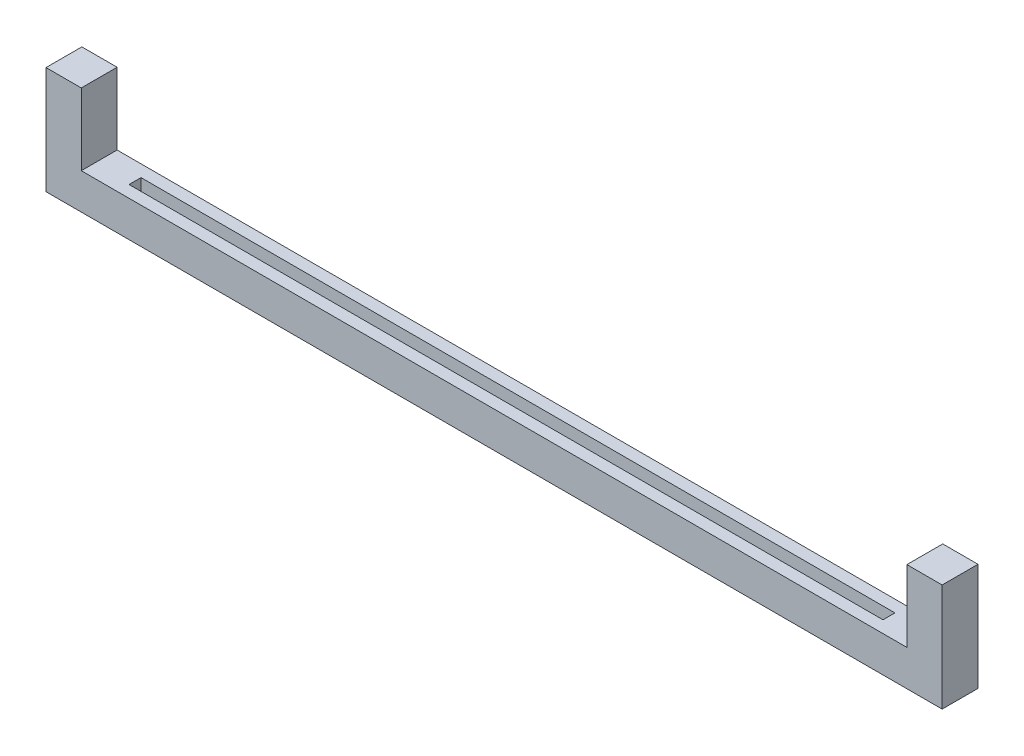
SolidWorks part; units mm, degrees
ref_plane "Front Plane" through (0, 0, 0) normal (0, 0, 1) x (1, 0, 0)
ref_plane "Top Plane" through (0, 0, 0) normal (0, 1, 0) x (1, 0, 0)
ref_plane "Right Plane" through (0, 0, 0) normal (1, 0, 0) x (0, 0, -1)
sketch "Sketch1" plane through (0, 0, 0) normal (0, 0, 1) x (1, 0, 0)
  line L0 (-62.5, 7.5) -> (62.5, -7.5) construction
  line L1 (-62.5, 7.5) -> (62.5, 7.5)
  line L2 (-62.5, 7.5) -> (-62.5, -7.5)
  line L3 (-62.5, -7.5) -> (62.5, -7.5)
  line L4 (62.5, 7.5) -> (62.5, -7.5)
  line L5 (62.5, 7.5) -> (-62.5, -7.5) construction
  line L7 (-57.58, 2.5) -> (57.58, 2.5)
  line L8 (-57.58, 2.5) -> (-57.58, -2.5)
  line L9 (-57.58, -2.5) -> (57.58, -2.5)
  line L10 (57.58, 2.5) -> (57.58, -2.5)
  point P4 (0, 0)
  dimension "D1" = 125
  dimension "D2" = 15
  dimension "D3" = 4.92
  dimension "D4" = 5
  dimension "D5" = 5
  dimension "D6" = 4.92
extrude "Slider Main Body" add sketch "Sketch1" along normal blind 5
sketch "Sketch5" plane through (0, -7.5, 0) normal (0, -1, 0) x (1, 0, 0)
  line L0 (57.58, 5) -> (57.58, 0) construction
  line L2 (57.58, 5) -> (57.58, 0)
  line L4 (62.5, 5) -> (-62.5, 5)
  line L5 (-62.5, 5) -> (-62.5, 0)
  line L6 (-62.5, 0) -> (62.5, 0)
  line L7 (62.5, 0) -> (62.5, 5)
  line L8 (57.58, 5) -> (-52.58, 5)
  line L10 (-52.58, 0) -> (57.58, 0)
  line L12 (52.58, 5) -> (52.58, 0)
  line L13 (-62.5, 5) -> (62.5, 5) construction
  line L14 (-52.58, 3.3333) -> (52.58, 3.3333)
  line L16 (-52.58, 1.6667) -> (52.58, 1.6667)
  line L17 (52.58, 3.3333) -> (52.58, 1.6667)
  line L18 (-62.5, 0) -> (62.5, 0) construction
  line L19 (-57.58, 5) -> (-57.58, 0) construction
  line L20 (-57.58, 5) -> (-57.58, 0)
  line L21 (-57.58, 5) -> (-52.58, 5)
  line L22 (-52.58, 5) -> (-52.58, 0)
  line L23 (-52.58, 0) -> (-57.58, 0)
  point P14 (0, 0)
  point P18 (0, 0)
  point P19 (0, 0)
  point P22 (0, 0)
  dimension "D5" = 5
  dimension "D2" = 5
  dimension "D3" = 1.6667
  dimension "D4" = 1.6667
extrude "Cut-Extrude1" cut sketch "Sketch5" against normal through all
sketch "Sketch6" plane through (0, 0, 5) normal (0, 0, 1) x (1, 0, 0)
  line L0 (62.5, 7.5) -> (-62.5, 7.5) construction
  line L1 (-57.58, 2.5) -> (57.58, 2.5)
  line L2 (-57.58, 2.5) -> (-57.58, 7.5)
  line L3 (-57.58, 7.5) -> (57.58, 7.5)
  line L4 (57.58, 2.5) -> (57.58, 7.5)
  line L5 (-57.58, 2.5) -> (57.58, 7.5) construction
  line L6 (-57.58, 7.5) -> (57.58, 2.5) construction
  line L7 (57.58, -2.5) -> (57.58, 2.5) construction
  point P4 (0, 5)
extrude "Cut-Extrude2" cut sketch "Sketch6" against normal through all
equation "\"Frame Side Length\"= \"Useful Tray Size\" + \"Universal Bar Height\" * 3"
equation "\"Universal Bar Height\"= 5mm"
equation "\"D1@Sketch1\"=\"Frame Side Length\"+\"Universal Bar Height\"*2"
equation "\"D2@Sketch1\"=\"Universal Bar Height\"*3"
equation "\"D3@Sketch1\"=\"Universal Bar Height\"- \"Slider Tolernace\"/2"
equation "\"D5@Sketch1\"=\"Universal Bar Height\""
equation "\"D6@Sketch1\"=\"Universal Bar Height\" - \"Slider Tolernace\"/2"
equation "\"D1@Slider Main Body\" = \"Universal Bar Height\""
equation "\"Useful Tray Size\"= 100mm"
equation "\"D2@Sketch5\"=\"Universal Bar Height\""
equation "\"D3@Sketch5\"=\"Universal Bar Height\"/3"
equation "\"D4@Sketch5\"=\"Universal Bar Height\"/3"
equation "\"D5@Sketch5\"=\"Universal Bar Height\""
equation "\"Slider Tolernace\"= 0.16mm'The total extra width of the inside of the slider (so it won't grip the frame too much"
